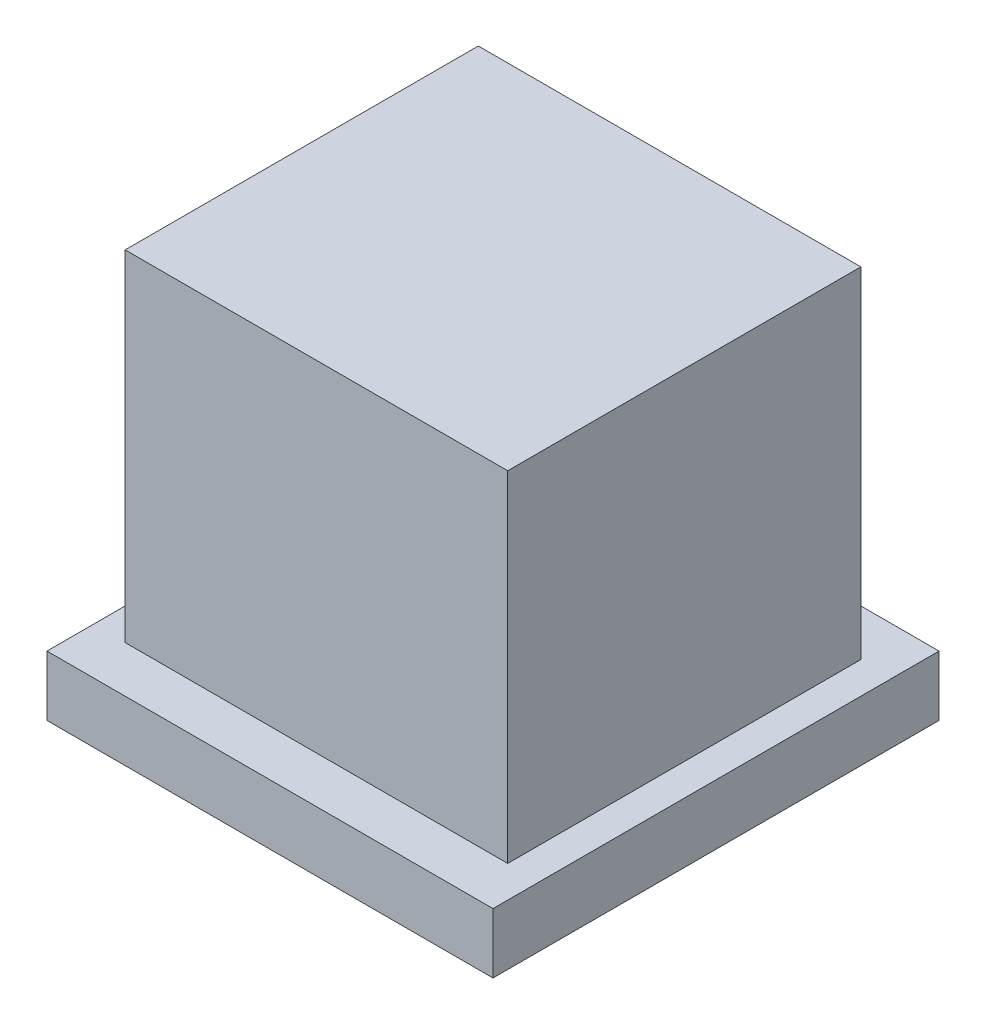
SolidWorks part; units mm, degrees
ref_plane "Front Plane" through (0, 0, 0) normal (0, 0, 1) x (1, 0, 0)
ref_plane "Top Plane" through (0, 0, 0) normal (0, 1, 0) x (1, 0, 0)
ref_plane "Right Plane" through (0, 0, 0) normal (1, 0, 0) x (0, 0, -1)
sketch "Sketch1" plane through (0, 0, 0) normal (0, 1, 0) x (1, 0, 0)
  line L1 (0, 0) -> (26.9494, 0)
  line L2 (0, 0) -> (0, 26.9494)
  line L3 (0, 26.9494) -> (26.9494, 26.9494)
  line L4 (26.9494, 0) -> (26.9494, 26.9494)
  dimension "D1" = 26.9494
  dimension "D2" = 26.9494
extrude "Boss-Extrude1" add sketch "Sketch1" along normal blind 3.6322
sketch "Sketch2" plane through (0, 3.6322, 0) normal (0, 1, 0) x (1, 0, 0)
  line L0 (0, 0) -> (26.9494, 26.9494) construction
  line L2 (1.9177, 24.1427) -> (25.0317, 24.1427)
  line L3 (1.9177, 24.1427) -> (1.9177, 2.8067)
  line L4 (1.9177, 2.8067) -> (25.0317, 2.8067)
  line L5 (25.0317, 24.1427) -> (25.0317, 2.8067)
  line L6 (1.9177, 24.1427) -> (25.0317, 2.8067) construction
  line L7 (1.9177, 2.8067) -> (25.0317, 24.1427) construction
  point P4 (13.4747, 13.4747)
  dimension "D1" = 21.336
  dimension "D2" = 23.114
extrude "Boss-Extrude2" add sketch "Sketch2" along normal blind 20.5486 contours L3 L4 L5 L2
sketch "Sketch3" plane through (0, 0, 0) normal (0, -1, 0) x (1, 0, 0)
  line L0 (13.4747, 0) -> (13.4747, -26.9494) construction
  line L1 (6.0635, -4.4342) -> (9.1076, -4.4342)
  line L2 (6.0635, -4.4342) -> (6.0635, -14.1068)
  line L3 (6.0635, -14.1068) -> (9.1076, -14.1068)
  line L4 (9.1076, -4.4342) -> (9.1076, -14.1068)
  line L5 (0, 0) -> (26.9494, 0) construction
  line L6 (26.9494, -26.9494) -> (0, -26.9494) construction
  line L7 (17.8418, -4.4342) -> (17.8418, -14.1068)
  line L8 (20.8859, -14.1068) -> (17.8418, -14.1068)
  line L9 (20.8859, -4.4342) -> (20.8859, -14.1068)
  line L10 (20.8859, -4.4342) -> (17.8418, -4.4342)
  circle A0 centre (13.4747, -19.7965) radius 2.2669
extrude "Cut-Extrude1" cut sketch "Sketch3" against normal blind 5
ref_plane "Plane1" through (13.4747, 0, 0) normal (-1, 0, 0) x (0, 0, 1)
ref_plane "Plane2" through (0, 0, -13.4747) normal (0, 0, 1) x (1, 0, 0)
equation "\"D2@Sketch1\"=\"D1@Sketch1\""
